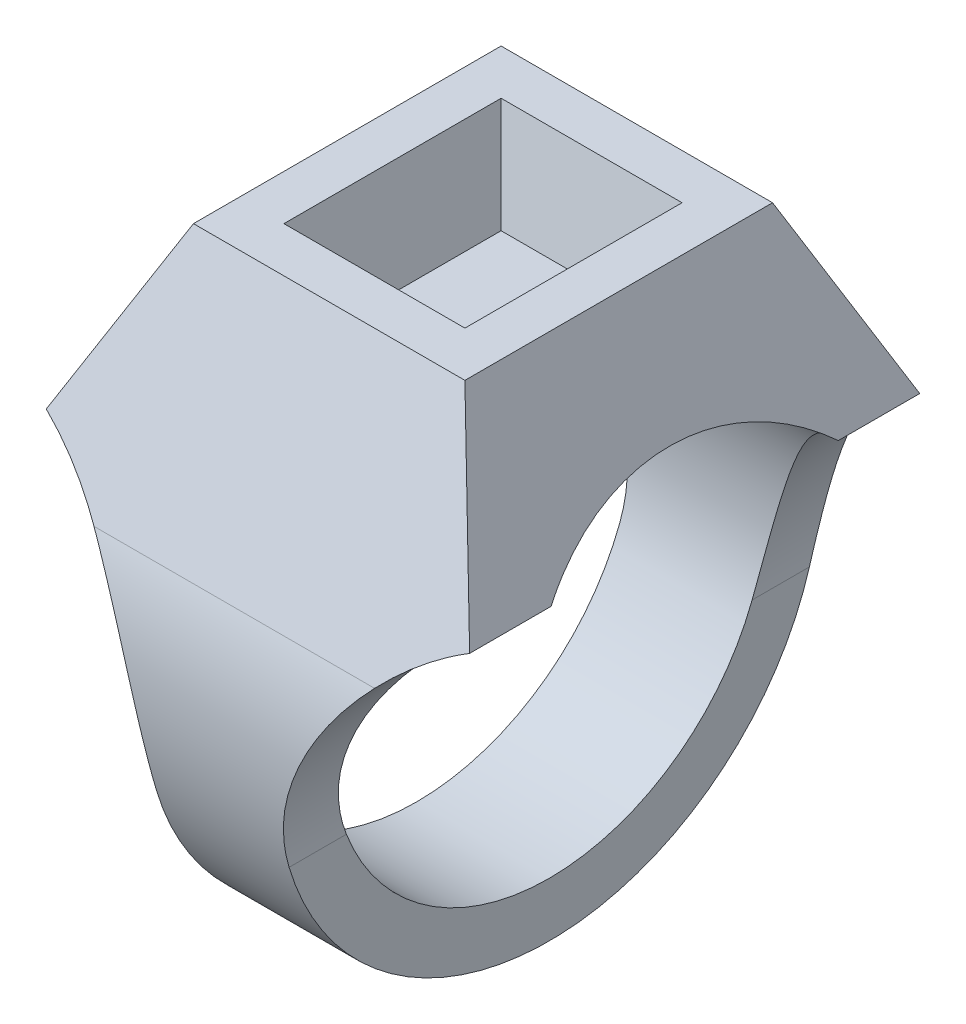
SolidWorks part; units mm, degrees
ref_plane "前视基准面" through (0, 0, 0) normal (0, 0, 1) x (1, 0, 0)
ref_plane "上视基准面" through (0, 0, 0) normal (0, 1, 0) x (1, 0, 0)
ref_plane "右视基准面" through (0, 0, 0) normal (1, 0, 0) x (0, 0, -1)
other "Configuration Table"
sketch "草图2" plane through (0, 0, 0) normal (1, 0, 0) x (0, 0, -1)
  line L0 (-13.7433, 6.0101) -> (-8.5, 18)
  line L1 (-8.5, 18) -> (8.5, 18)
  line L2 (0, 18) -> (0, 0) construction
  line L3 (13.7433, 6.0101) -> (8.5, 18)
  circle A0 centre (0, 0) radius 12
  arc A1 (-13.7433, 6.0101) -> (13.7433, 6.0101) centre (0, 0) ccw
  dimension "D1" = 30
  dimension "D2" = 24
  dimension "D3" = 18
  dimension "D4" = 17
extrude "凸台-拉伸1" add sketch "草图2" along normal mid plane 50
sketch "草图3" plane through (0, 18, 0) normal (0, 1, 0) x (1, 0, 0)
  line L1 (-5, 6) -> (5, 6)
  line L2 (-5, 6) -> (-5, -6)
  line L3 (-5, -6) -> (5, -6)
  line L4 (5, 6) -> (5, -6)
  line L5 (-5, 6) -> (5, -6) construction
  line L6 (-5, -6) -> (5, 6) construction
  point P0 (0, 0)
  dimension "D1" = 12
  dimension "D2" = 10
extrude "切除-拉伸1" cut sketch "草图3" against normal blind 5 draft 15
sketch "草图4" plane through (0, 0, 0) normal (0, 0, 1) x (1, 0, 0)
  line L0 (0, 32.9584) -> (0, -23.6968) construction
  line L1 (7.5, 18) -> (-7.5, 18)
  line L2 (25, 18) -> (-25, 18) construction
  line L3 (-7.5, 18) -> (-11.6968, 9)
  line L4 (-3.6603, -4.2857) -> (-3.6603, -15)
  line L5 (-25, -15) -> (25, -15) construction
  line L6 (-3.6603, -15) -> (3.6603, -15)
  line L7 (3.6603, -4.2857) -> (3.6603, -15)
  line L8 (7.5, 18) -> (11.6968, 9)
  arc A0 (-11.6968, 9) -> (-3.6603, -4.2857) centre (-18.6603, -4.2857) cw
  arc A1 (11.6968, 9) -> (3.6603, -4.2857) centre (18.6603, -4.2857) ccw
  point P10 (-3.6603, -9.6429)
  point P14 (-3.6603, 0)
  point P22 (0, -15)
  point P23 (0, 18)
  dimension "D1" = 15
  dimension "D2" = 9
  dimension "D3" = 15
  dimension "D4" = 65
extrude "切除-拉伸2" cut sketch "草图4" against normal through all both and the other way through all flip side to cut
